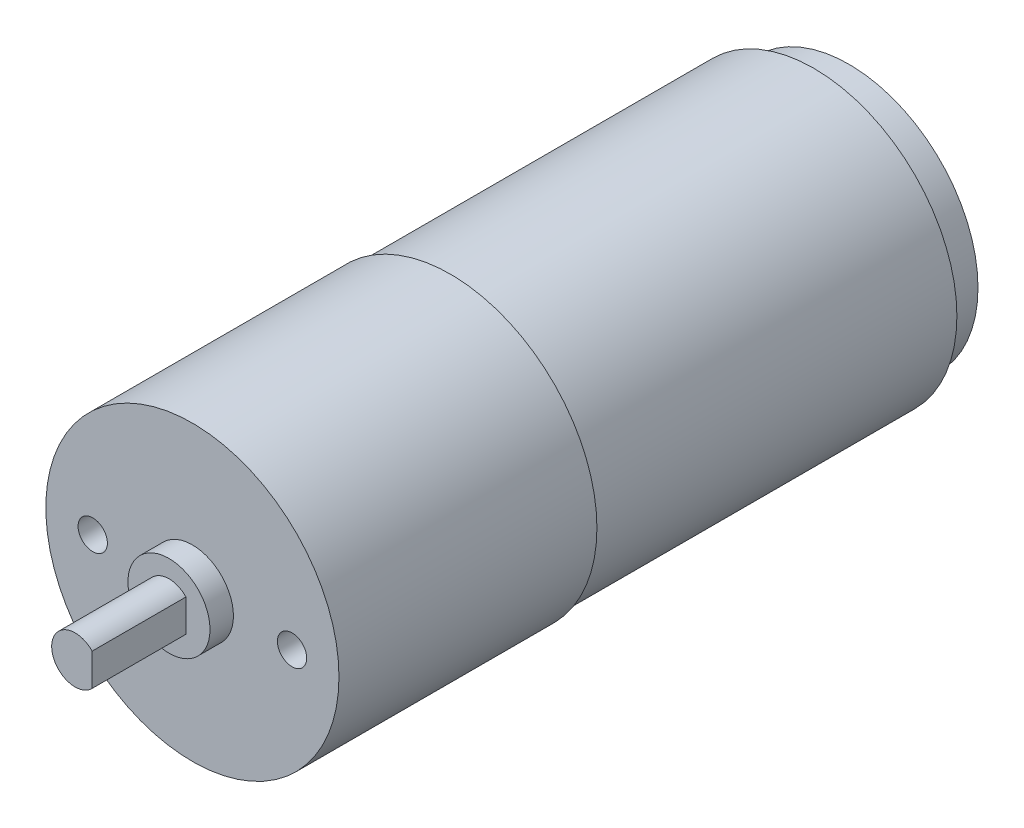
SolidWorks part; units mm, degrees
ref_plane "Front Plane" through (0, 0, 0) normal (0, 0, 1) x (1, 0, 0)
ref_plane "Top Plane" through (0, 0, 0) normal (0, 1, 0) x (1, 0, 0)
ref_plane "Right Plane" through (0, 0, 0) normal (1, 0, 0) x (0, 0, -1)
ref_plane "P_Front_m22" through (0, 0, -22) normal (0, 0, 1) x (1, 0, 0)
sketch "Sketch1" plane through (0, 0, -22) normal (0, 0, 1) x (1, 0, 0)
  circle A0 centre (0, 0) radius 12.5
extrude "Gearbox" add sketch "Sketch1" along normal blind 22
ref_plane "P_Front_m53" through (0, 0, -53) normal (0, 0, 1) x (1, 0, 0)
sketch "Sketch2" plane through (0, 0, -53) normal (0, 0, 1) x (1, 0, 0)
  circle A0 centre (0, 0) radius 12.2
extrude "Can" add sketch "Sketch2" along normal blind 31
ref_plane "P_Front_m56" through (0, 0, -56) normal (0, 0, 1) x (1, 0, 0)
sketch "Sketch3" plane through (0, 0, -56) normal (0, 0, 1) x (1, 0, 0)
  circle A0 centre (0, 0) radius 11
extrude "End_cap" add sketch "Sketch3" along normal blind 3
sketch "Sketch4" plane through (0, 0, 0) normal (0, 0, 1) x (1, 0, 0)
  circle A0 centre (0, 0) radius 3.5
extrude "Bearing_boss" add sketch "Sketch4" along normal blind 2
ref_plane "P_Front_2" through (0, 0, 2) normal (0, 0, 1) x (1, 0, 0)
sketch "Sketch5" plane through (0, 0, 2) normal (0, 0, 1) x (1, 0, 0)
  line L0 (1.45, -1.3775) -> (1.45, 1.3775)
  arc A0 (1.45, 1.3775) -> (1.45, -1.3775) centre (0, 0) ccw
extrude "Shaft_4mm_D" add sketch "Sketch5" along normal blind 8
sketch "Sketch6" plane through (0, 0, 0) normal (0, 0, 1) x (1, 0, 0)
  circle A0 centre (-8.5, 0) radius 1.25
  circle A1 centre (8.5, 0) radius 1.25
extrude "M3_face_holes" cut sketch "Sketch6" against normal blind 5
